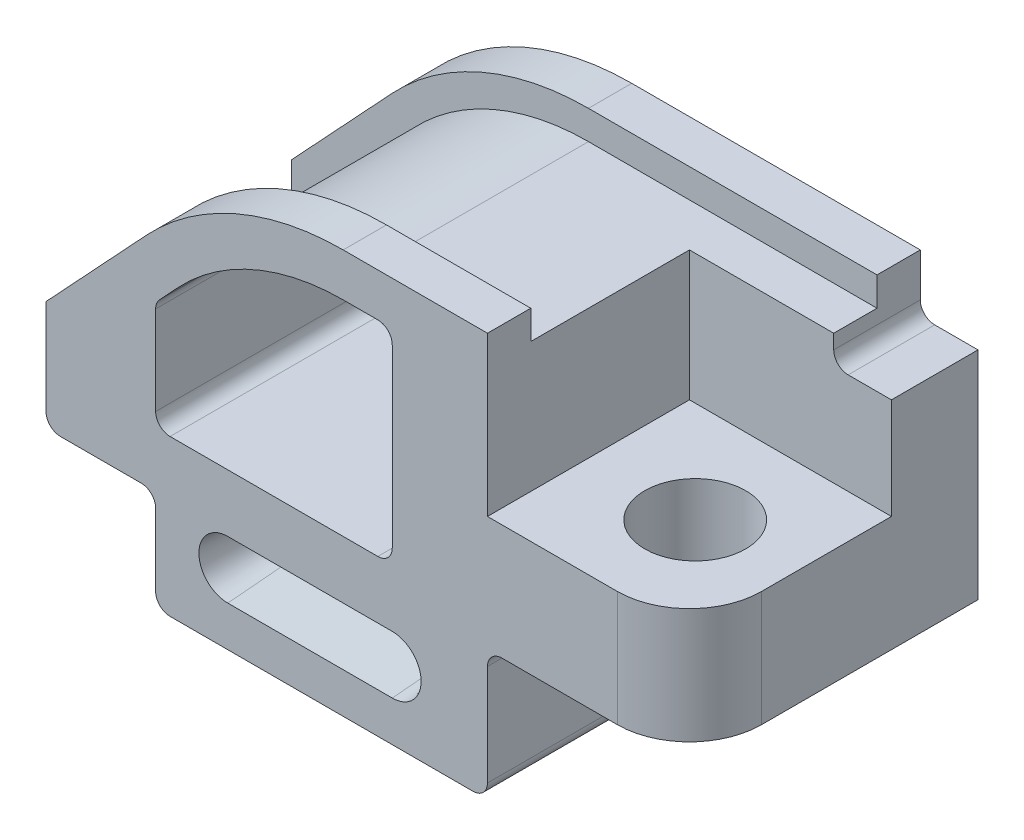
SolidWorks part; units mm, degrees
material "Copper"
ref_plane "Front Plane" through (0, 0, 0) normal (0, 0, 1) x (1, 0, 0)
ref_plane "Top Plane" through (0, 0, 0) normal (0, 1, 0) x (1, 0, 0)
ref_plane "Right Plane" through (0, 0, 0) normal (1, 0, 0) x (0, 0, -1)
sketch "Sketch1" plane through (0, 0, 0) normal (0, 0, 1) x (1, 0, 0)
  line L0 (0, 0) -> (38, 0)
  line L1 (38, 0) -> (38, -35)
  line L2 (38, -35) -> (153, -35)
  line L3 (153, -35) -> (153, 10)
  line L4 (153, 10) -> (223, 10)
  line L5 (223, 10) -> (223, 85)
  line L6 (223, 85) -> (203, 85)
  line L7 (203, 85) -> (203, 105)
  line L8 (203, 105) -> (103, 105)
  line L9 (34.8429, 75.3645) -> (0, 38)
  line L10 (0, 38) -> (0, 0)
  arc A0 (103, 105) -> (34.8429, 75.3645) centre (103, 11.807) ccw
  point P13 (36.3952, 91.606)
  point P14 (223, 47.5)
  dimension "D1" = 35
  dimension "D2" = 115
  dimension "D3" = 70
  dimension "D4" = 75
  dimension "D5" = 45
  dimension "D6" = 20
  dimension "D7" = 100
  dimension "D8" = 140
  dimension "D9" = 223
  dimension "D10" = 38
  dimension "D11" = 43
extrude "Boss-Extrude1" add sketch "Sketch1" along normal mid plane 100
sketch "Sketch2" plane through (0, 0, 50) normal (0, 0, 1) x (1, 0, 0)
  line L6 (38, 56.7558) -> (38, 19)
  line L7 (38, 19) -> (120, 19)
  line L8 (203, 90) -> (103, 90)
  line L9 (45.8132, 65.1345) -> (10.9703, 27.77)
  line L10 (120, 90) -> (103, 90)
  line L11 (45.8132, 65.1345) -> (38, 56.7558)
  line L12 (120, 19) -> (120, 90)
  line L13 (38, 0) -> (38, -35) construction
  line L14 (153, -35) -> (153, 10) construction
  line L15 (0, 38) -> (0, 0) construction
  arc A4 (103, 90) -> (45.8132, 65.1345) centre (103, 11.807) ccw
  arc A5 (103, 90) -> (45.8132, 65.1345) centre (103, 11.807) ccw
  point P15 (0, 19)
  dimension "D2" = 33
  dimension "D1" = 15
extrude "Cut-Extrude1" cut sketch "Sketch2" against normal offset from surface (85 mm away) 15 up to face at (114.0634, 37.5377, -50)
sketch "Sketch4" plane through (0, 0, 0) normal (0, 0, 1) x (1, 0, 0)
  line L2 (203, 85) -> (203, 105) construction
  line L3 (203, 105) -> (103, 105) construction
  line L4 (203, 95) -> (103, 95)
  line L5 (42.1565, 68.5445) -> (7.3135, 31.18)
  line L6 (203, 95) -> (103, 95)
  line L7 (42.1565, 68.5445) -> (0, 23.3372)
  line L8 (34.8429, 75.3645) -> (0, 38) construction
  line L9 (0, 38) -> (0, 0) construction
  line L10 (203, 95) -> (203, 105)
  line L11 (203, 105) -> (103, 105)
  line L12 (34.8429, 75.3645) -> (0, 38)
  line L13 (0, 38) -> (0, 23.3372)
  arc A1 (103, 105) -> (34.8429, 75.3645) centre (103, 11.807) ccw construction
  arc A2 (103, 95) -> (42.1565, 68.5445) centre (103, 11.807) ccw
  arc A3 (103, 95) -> (42.1565, 68.5445) centre (103, 11.807) ccw
  arc A4 (103, 105) -> (34.8429, 75.3645) centre (103, 11.807) ccw
  dimension "D1" = 10
extrude "Cut-Extrude2" cut sketch "Sketch4" against normal mid plane 70
sketch "Sketch5" plane through (0, 105, 0) normal (0, 1, 0) x (1, 0, 0)
  line L1 (223, -50) -> (153, -50)
  line L2 (223, -50) -> (223, 20)
  line L3 (223, 20) -> (153, 20)
  line L4 (153, -50) -> (153, 20)
  dimension "D1" = 70
extrude "Cut-Extrude3" cut sketch "Sketch5" against normal blind 55
sketch "Sketch6" plane through (0, 50, 0) normal (0, 1, 0) x (1, 0, 0)
  line L0 (153, -50) -> (223, 20) construction
  circle A0 centre (190, -15) radius 17.5
  point P6 (0, 0)
  point P7 (0, 0)
  dimension "D1" = 35
extrude "Cut-Extrude4" cut sketch "Sketch6" against normal through all
fillet "Fillet1" radius 25 1 edges at (223, 30, 50)
fillet "Fillet2" radius 5 6 edges at (153, 10, 0) (153, -35, 0) (38, -35, 0) (0, 0, 0) (38, 0, 0) (203, 85, -35)
fillet "Fillet3" radius 5 4 edges at (120, 19, 7.5) (120, 90, 7.5) (38, 19, 7.5) (38, 56.7558, 7.5)
sketch "Sketch7" plane through (0, 0, 50) normal (0, 0, 1) x (1, 0, 0)
  line L0 (63, -11) -> (120, -11) construction
  line L1 (63, -1) -> (120, -1)
  line L2 (63, -21) -> (120, -21)
  line L3 (43, 19) -> (115, 19) construction
  line L4 (38, -5) -> (38, -30) construction
  arc A0 (63, -1) -> (63, -21) centre (63, -11) ccw
  arc A1 (120, -21) -> (120, -1) centre (120, -11) ccw
  point P2 (91.5, -11)
  dimension "D4" = 10
  dimension "D1" = 20
  dimension "D2" = 25
  dimension "D3" = 57
extrude "Cut-Extrude5" cut sketch "Sketch7" against normal blind 25 draft 5
mirror "Mirror1" about plane through (0, 0, 0) normal (0, 0, 1) of "Cut-Extrude5"
equation "\"A\" = 223"
equation "\"B\" = 38"
equation "\"C\" = 35"
equation "\"D\"= 43"
equation "\"D9@Sketch1\"=\"A\""
equation "\"D10@Sketch1\"=\"B\""
equation "\"D11@Sketch1\"=\"D\""
equation "\"D1@Sketch6\"=\"C\""
